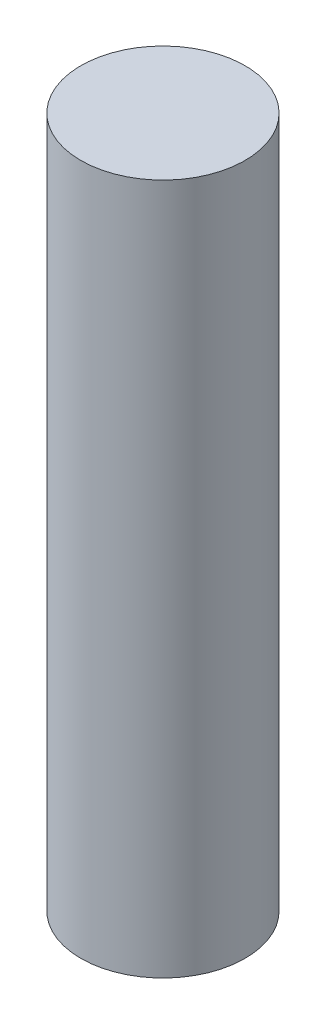
SolidWorks part; units mm, degrees
material "6061 Alloy"
ref_plane "Front Plane" through (0, 0, 0) normal (0, 0, 1) x (1, 0, 0)
ref_plane "Top Plane" through (0, 0, 0) normal (0, 1, 0) x (1, 0, 0)
ref_plane "Right Plane" through (0, 0, 0) normal (1, 0, 0) x (0, 0, -1)
sketch "Sketch1" plane through (0, 0, 0) normal (0, 1, 0) x (1, 0, 0)
  circle A0 centre (-1.8696, 3.1726) radius 4
  dimension "D1" = 8
extrude "Boss-Extrude1" add sketch "Sketch1" along normal blind 33.655
